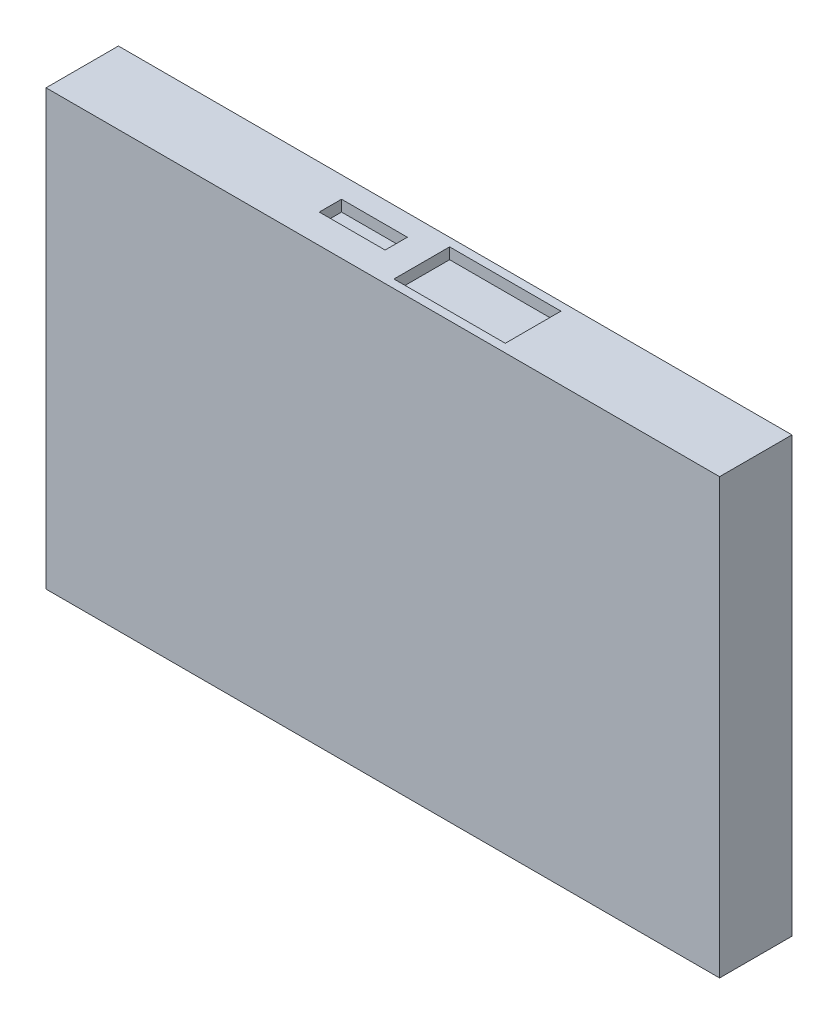
SolidWorks part; units mm, degrees
ref_plane "Front Plane" through (0, 0, 0) normal (0, 0, 1) x (1, 0, 0)
ref_plane "Top Plane" through (0, 0, 0) normal (0, 1, 0) x (1, 0, 0)
ref_plane "Right Plane" through (0, 0, 0) normal (1, 0, 0) x (0, 0, -1)
sketch "Sketch1" plane through (0, 0, 0) normal (0, 0, 1) x (1, 0, 0)
  line L1 (0, 0) -> (121, 0)
  line L2 (0, 0) -> (0, 78)
  line L3 (0, 78) -> (121, 78)
  line L4 (121, 0) -> (121, 78)
  dimension "D1" = 121
  dimension "D2" = 78
extrude "Boss-Extrude1" add sketch "Sketch1" along normal blind 13
sketch "Sketch2" plane through (0, 0, 0) normal (0, 0, -1) x (-1, 0, 0)
  line L0 (0, 0) -> (-121, 0) construction
  line L1 (-3, 3) -> (-118, 3)
  line L2 (-3, 3) -> (-3, 73)
  line L3 (-3, 73) -> (-118, 73)
  line L4 (-118, 3) -> (-118, 73)
  line L5 (-121, 0) -> (-121, 78) construction
  line L6 (0, 78) -> (0, 0) construction
  line L7 (-121, 78) -> (0, 78) construction
  point P10 (0, 39)
  dimension "D1" = 3
  dimension "D2" = 3
  dimension "D3" = 3
  dimension "D4" = 5
extrude "Cut-Extrude1" cut sketch "Sketch2" against normal blind 1
sketch "Sketch4" plane through (0, 78, 0) normal (0, 1, 0) x (1, 0, 0)
  line L1 (81, -11.5) -> (61, -11.5)
  line L2 (81, -11.5) -> (81, -1.5)
  line L3 (81, -1.5) -> (61, -1.5)
  line L4 (61, -11.5) -> (61, -1.5)
  line L5 (121, -13) -> (0, -13) construction
  line L7 (121, -13) -> (121, 0) construction
  line L9 (55.7033, -7.7897) -> (43.8784, -7.7897)
  line L10 (55.7033, -7.7897) -> (55.7033, -3.7925)
  line L11 (55.7033, -3.7925) -> (43.8784, -3.7925)
  line L12 (43.8784, -7.7897) -> (43.8784, -3.7925)
  dimension "D1" = 20
  dimension "D2" = 10
  dimension "D3" = 1.5
  dimension "D4" = 40
extrude "Cut-Extrude2" cut sketch "Sketch4" against normal blind 2
